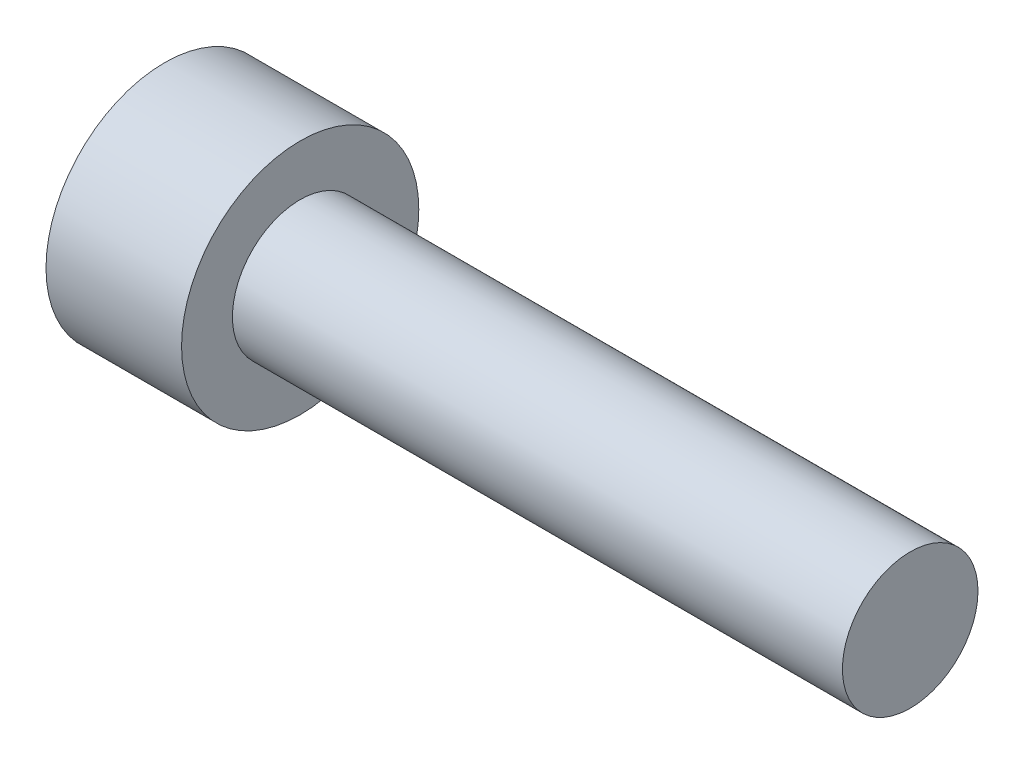
SolidWorks part; units mm, degrees
material "AISI 304"
ref_plane "Front Plane" through (0, 0, 0) normal (0, 0, 1) x (1, 0, 0)
ref_plane "Top Plane" through (0, 0, 0) normal (0, 1, 0) x (1, 0, 0)
ref_plane "Right Plane" through (0, 0, 0) normal (1, 0, 0) x (0, 0, -1)
sketch "草图1" plane through (0, 0, 0) normal (1, 0, 0) x (0, 0, -1)
  circle A0 centre (0, 0) radius 3.5
  dimension "D1" = 7
extrude "凸台-拉伸1" add sketch "草图1" along normal blind 4
sketch "草图2" plane through (0, 0, 0) normal (-1, 0, 0) x (0, 0, 1)
  line L1 (1.525, -0.8805) -> (1.525, 0.8805)
  line L2 (1.525, 0.8805) -> (0, 1.7609)
  line L3 (0, 1.7609) -> (-1.525, 0.8805)
  line L4 (-1.525, 0.8805) -> (-1.525, -0.8805)
  line L5 (-1.525, -0.8805) -> (0, -1.7609)
  line L6 (0, -1.7609) -> (1.525, -0.8805)
  circle A0 centre (0, 0) radius 1.525 construction
  dimension "D1" = 3.05
extrude "切除-拉伸1" cut sketch "草图2" against normal blind 2
sketch "草图3" plane through (4, 0, 0) normal (1, 0, 0) x (0, 0, -1)
  circle A0 centre (0, 0) radius 2
  dimension "D1" = 4
extrude "凸台-拉伸2" add sketch "草图3" along normal blind 18
cosmetic thread "装饰螺纹线1" parameters "D2"=4
